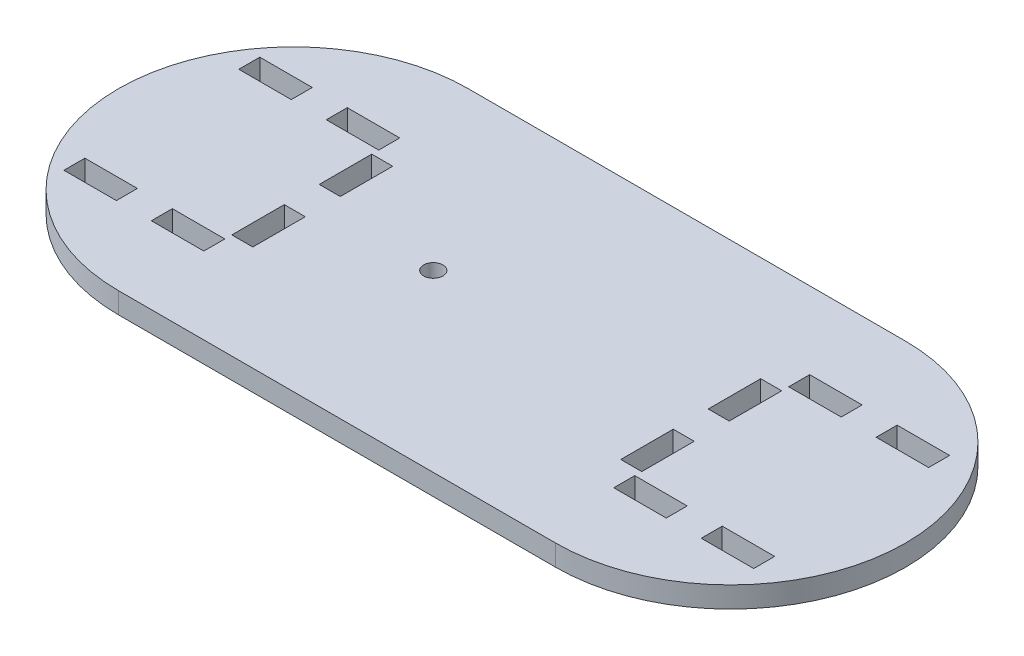
SolidWorks part; units mm, degrees
material "6061-T6 (SS)"
ref_plane "Alzado" through (0, 0, 0) normal (0, 0, 1) x (1, 0, 0)
ref_plane "Planta" through (0, 0, 0) normal (0, 1, 0) x (1, 0, 0)
ref_plane "Vista lateral" through (0, 0, 0) normal (1, 0, 0) x (0, 0, -1)
sketch "Croquis1" plane through (0, 0, 0) normal (0, 1, 0) x (1, 0, 0)
  line L0 (-40, 50) -> (85, 50)
  line L1 (85, -50) -> (-40, -50)
  arc A0 (-40, 50) -> (-40, -50) centre (-40, 0) ccw
  arc A2 (85, 50) -> (85, -50) centre (85, 0) cw
  dimension "D1" = 100
  dimension "D2" = 50
  dimension "D3" = 85
  dimension "D4" = 40
extrude "Saliente-Extruir1" add sketch "Croquis1" along normal mid plane 6
hole_wizard "Taladro de margen para M51" positions "Croquis5" profile "Croquis6" hole size "M5" standard "Ansi Metric" end condition up to next
sketch "Croquis5" plane through (0, 3, 0) normal (0, 1, 0) x (1, 0, 0)
  point P0 (0, 0)
sketch "Croquis6" plane through (0, 3, 0) normal (1, 0, 0) x (0, 0, 1)
  line L0 (0, 0) -> (0, 6)
  line L1 (0, 6) -> (2.75, 6)
  line L2 (2.75, 6) -> (2.75, 0)
  line L5 (2.75, 0) -> (0, 0)
  line L11 (0, -6.35) -> (0, 107.95) construction
  dimension "Diámetro de taladro hasta el siguiente" = 5.5
  dimension "Profundidad de taladro hasta el siguiente" = 6
ref_plane "Plano1" through (21, 0, 0) normal (1, 0, 0) x (0, 0, -1)
sketch "Croquis7" plane through (0, -3, 0) normal (0, -1, 0) x (-1, 0, 0)
  line L0 (0, 0) -> (-135, 0) construction
  line L1 (-79.5937, -28) -> (-94.5937, -28)
  line L2 (-79.5937, -28) -> (-79.5937, -22)
  line L3 (-79.5937, -22) -> (-94.5937, -22)
  line L4 (-94.5937, -28) -> (-94.5937, -22)
  line L5 (-104.5937, -28) -> (-119.5937, -28)
  line L6 (-104.5937, -28) -> (-104.5937, -22)
  line L7 (-104.5937, -22) -> (-119.5937, -22)
  line L8 (-119.5937, -28) -> (-119.5937, -22)
  line L9 (-104.5937, 22) -> (-119.5937, 22)
  line L10 (-119.5937, 28) -> (-119.5937, 22)
  line L11 (-104.5937, 28) -> (-119.5937, 28)
  line L12 (-104.5937, 28) -> (-104.5937, 22)
  line L13 (-79.5937, 22) -> (-94.5937, 22)
  line L14 (-94.5937, 28) -> (-94.5937, 22)
  line L15 (-79.5937, 28) -> (-94.5937, 28)
  line L16 (-79.5937, 28) -> (-79.5937, 22)
  line L18 (-73.5937, -20) -> (-79.5937, -20)
  line L19 (-73.5937, -20) -> (-73.5937, -5)
  line L20 (-73.5937, -5) -> (-79.5937, -5)
  line L21 (-79.5937, -20) -> (-79.5937, -5)
  line L22 (-73.5937, 5) -> (-79.5937, 5)
  line L23 (-73.5937, 5) -> (-73.5937, 20)
  line L24 (-73.5937, 20) -> (-79.5937, 20)
  line L25 (-79.5937, 5) -> (-79.5937, 20)
  arc A0 (-85, 50) -> (-85, -50) centre (-85, 0) ccw construction
extrude "Cortar-Extruir1" cut sketch "Croquis7" against normal through all
mirror "Simetría1" about plane through (21, 0, 0) normal (1, 0, 0) of "Cortar-Extruir1"
